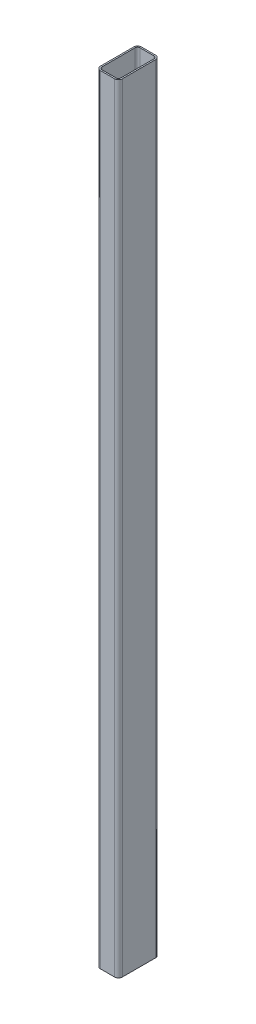
SolidWorks part; units mm, degrees
ref_plane "Front Plane" through (0, 0, 0) normal (0, 0, 1) x (1, 0, 0)
ref_plane "Top Plane" through (0, 0, 0) normal (0, 1, 0) x (1, 0, 0)
ref_plane "Right Plane" through (0, 0, 0) normal (1, 0, 0) x (0, 0, -1)
sketch "Sketch6" plane through (0, 0, 0) normal (0, 1, 0) x (1, 0, 0)
  line L1 (-15, -40) -> (15, -40)
  line L2 (-20, -35) -> (-20, 35)
  line L3 (-15, 40) -> (15, 40)
  line L4 (20, -35) -> (20, 35)
  line L5 (-20, -40) -> (20, 40) construction
  line L6 (-20, 40) -> (20, -40) construction
  arc A0 (-20, -35) -> (-15, -40) centre (-15, -35) ccw
  arc A1 (15, -40) -> (20, -35) centre (15, -35) ccw
  arc A2 (15, 40) -> (20, 35) centre (15, 35) cw
  arc A3 (-15, 40) -> (-20, 35) centre (-15, 35) ccw
  point P0 (0, 0)
  dimension "D3" = 5
  dimension "D1" = 40
  dimension "D2" = 80
extrude "Extrude-Thin1" add sketch "Sketch6" along normal blind 1634 thin
sketch "Sketch7" plane through (-23, 0, 0) normal (-1, 0, 0) x (0, 0, 1)
  line L0 (55, 0) -> (-55, 0) construction
  circle A0 centre (0, 35) radius 5
  circle A1 centre (0, 75) radius 5
  point P4 (0, 0)
  dimension "D1" = 10
  dimension "D2" = 35
  dimension "D3" = 40
extrude "Cut-Extrude1" cut sketch "Sketch7" against normal up to next
